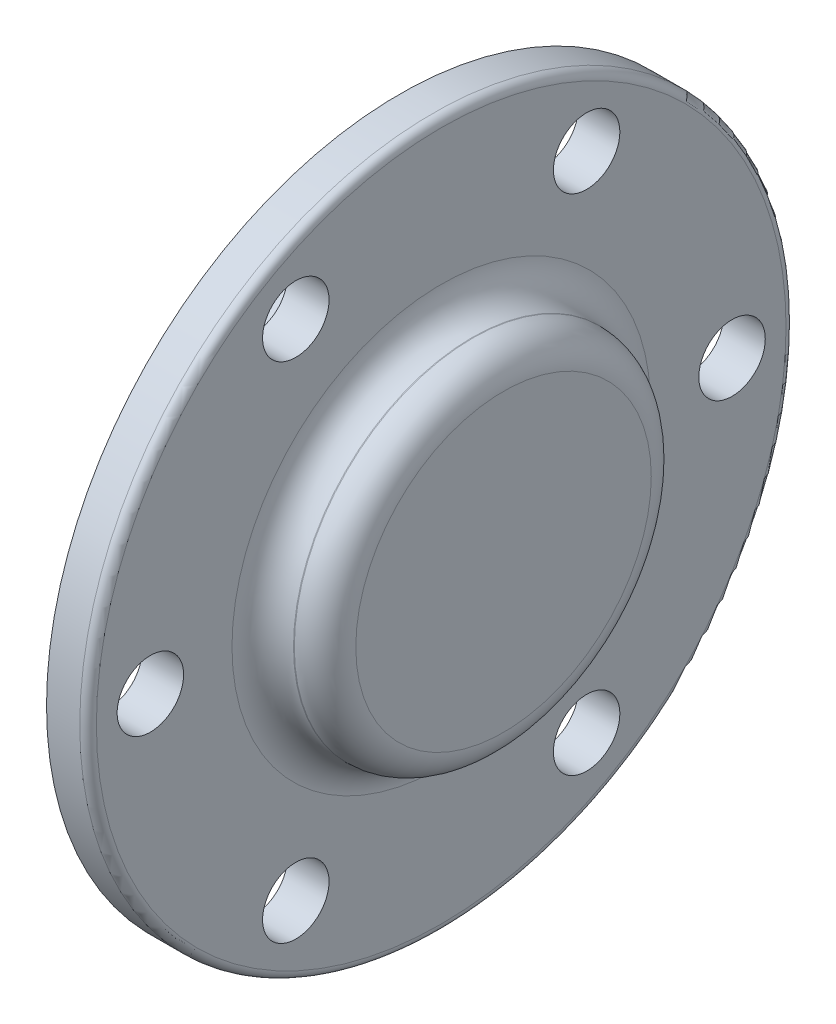
SolidWorks part; units mm, degrees
ref_plane "Front Plane" through (0, 0, 0) normal (0, 0, 1) x (1, 0, 0)
ref_plane "Top Plane" through (0, 0, 0) normal (0, 1, 0) x (1, 0, 0)
ref_plane "Right Plane" through (0, 0, 0) normal (1, 0, 0) x (0, 0, -1)
sketch "Sketch1" plane through (0, 0, 0) normal (0, 0, 1) x (1, 0, 0)
  line L0 (0, 0) -> (85.1756, 0) construction
  line L1 (0, 45) -> (23, 45)
  line L2 (23, 45) -> (23, 85)
  line L3 (23, 85) -> (31, 85)
  line L4 (33, 83) -> (33, 50.3601)
  line L14 (0, 39) -> (0, 45)
  line L17 (40.4, 42.9601) -> (40.6, 42.9601)
  line L18 (48, 35.5601) -> (48, 0)
  line L19 (0, 39) -> (32.5153, 30.2876)
  line L20 (38, 23.1397) -> (38, 0)
  arc A3 (31, 85) -> (33, 83) centre (31, 83) cw
  arc A4 (40.6, 42.9601) -> (48, 35.5601) centre (40.6, 35.5601) cw
  arc A5 (33, 50.3601) -> (40.4, 42.9601) centre (40.4, 50.3601) ccw
  arc A6 (32.5153, 30.2876) -> (38, 23.1397) centre (30.6, 23.1397) cw
  point P16 (33, 42.9601)
  point P21 (38, 28.8179)
  dimension "D3" = 10
  dimension "D9" = 7.4
  dimension "D11" = 2
  dimension "D2" = 78
  dimension "D4" = 15
  dimension "D5" = 15
  dimension "D6" = 90
  dimension "D7" = 15
  dimension "D8" = 170
  dimension "D10" = 10
  dimension "D15" = 23
revolve "Revolve1" add sketch "Sketch1" angle 360 about L0
sketch "Sketch2" plane through (33, 0, 0) normal (1, 0, 0) x (0, 0, -1)
  circle A0 centre (0, 0) radius 70 construction
  circle A1 centre (70, 0) radius 8
  circle A2 centre (35, -60.6218) radius 8
  circle A3 centre (-35, -60.6218) radius 8
  circle A4 centre (-70, 0) radius 8
  circle A5 centre (-35, 60.6218) radius 8
  circle A6 centre (35, 60.6218) radius 8
  point P5 (36.2502, 64.0619)
  point P6 (0, 0)
  point P18 (0, 0)
  dimension "D1" = 140
  dimension "D2" = 16
  dimension "D3" = 6
extrude "Cut-Extrude1" cut sketch "Sketch2" against normal through all both
